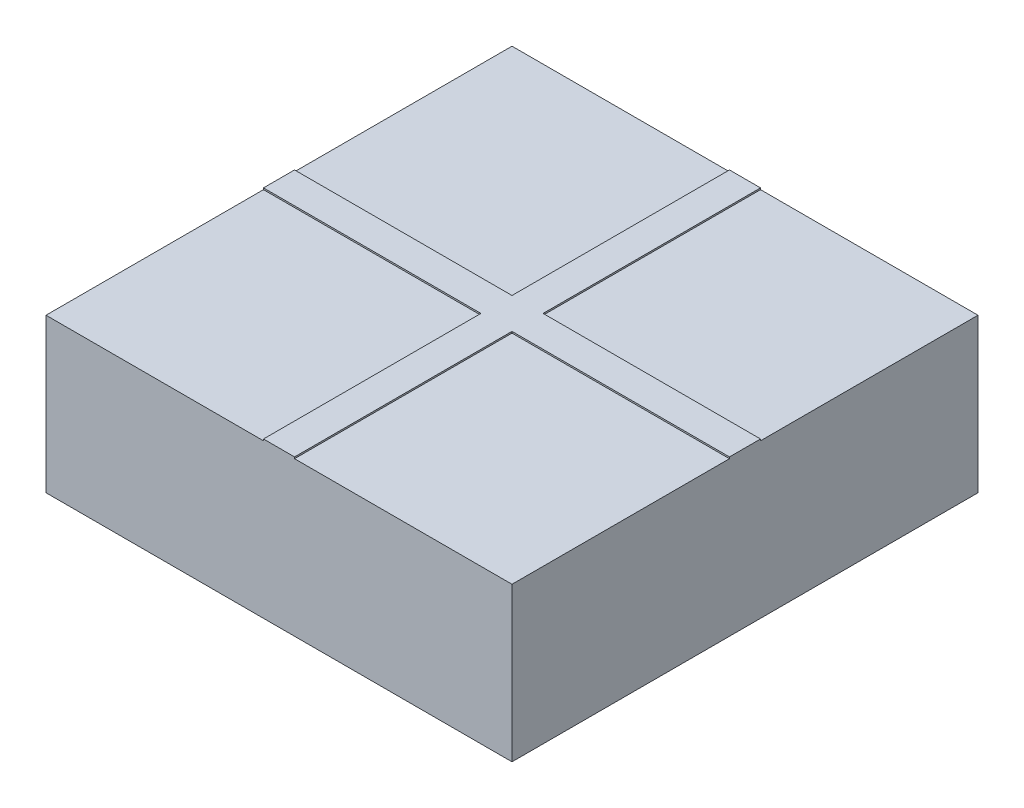
SolidWorks part; units mm, degrees
ref_plane "Спереди" through (0, 0, 0) normal (0, 0, 1) x (1, 0, 0)
ref_plane "Сверху" through (0, 0, 0) normal (0, 1, 0) x (1, 0, 0)
ref_plane "Справа" through (0, 0, 0) normal (1, 0, 0) x (0, 0, -1)
sketch "Эскиз1" plane through (0, 0, 0) normal (0, 1, 0) x (1, 0, 0)
  line L1 (-150, -150) -> (150, -150)
  line L2 (-150, -150) -> (-150, 150)
  line L3 (-150, 150) -> (150, 150)
  line L4 (150, -150) -> (150, 150)
  line L5 (-150, -150) -> (150, 150) construction
  line L6 (-150, 150) -> (150, -150) construction
  point P0 (0, 0)
  dimension "D1" = 300
extrude "Бобышка-Вытянуть1" add sketch "Эскиз1" along normal blind 90
sketch "Эскиз2" plane through (0, 90, 0) normal (0, 1, 0) x (1, 0, 0)
  line L1 (10, -150) -> (-10, -150)
  line L2 (10, -150) -> (10, 150)
  line L3 (10, 150) -> (-10, 150)
  line L4 (150, -150) -> (150, 150)
  line L5 (150, 150) -> (-150, 150)
  line L6 (-150, 150) -> (-150, -150)
  line L7 (-150, -150) -> (150, -150)
  line L8 (150, -150) -> (150, 150)
  line L9 (150, 150) -> (-150, 150)
  line L10 (-150, 150) -> (-150, -150)
  line L11 (-150, -150) -> (150, -150)
  line L12 (-10, -150) -> (-10, 150)
  line L13 (10, -150) -> (-10, 150) construction
  line L14 (10, 150) -> (-10, -150) construction
  line L15 (150, -10) -> (-150, -10)
  line L16 (150, -10) -> (150, 10)
  line L17 (150, 10) -> (-150, 10)
  line L18 (-150, -10) -> (-150, 10)
  line L19 (150, -10) -> (-150, 10) construction
  line L20 (150, 10) -> (-150, -10) construction
  point P2 (0, 0)
  point P10 (0, 0)
  point P15 (0, 0)
  dimension "D2" = 20
  dimension "D3" = 20
  dimension "D1" = 0
extrude "Бобышка-Вытянуть3" add sketch "Эскиз2" along normal blind 10 contours L12 L3 L2 L1 | L17 L18 L15 L16
sketch "Эскиз6" plane through (0, 90, 0) normal (0, 1, 0) x (1, 0, 0)
  line L0 (-150, -150) -> (-10, -150) construction
  line L1 (-10, -150) -> (-10, -10) construction
  line L2 (-10, -10) -> (-150, -10) construction
  line L3 (-150, -10) -> (-150, -150) construction
  line L4 (150, -150) -> (150, -10) construction
  line L5 (150, -10) -> (10, -10) construction
  line L6 (10, -10) -> (10, -150) construction
  line L7 (10, -150) -> (150, -150) construction
  line L8 (10, 150) -> (10, 10) construction
  line L9 (10, 10) -> (150, 10) construction
  line L10 (150, 10) -> (150, 150) construction
  line L11 (150, 150) -> (10, 150) construction
  line L12 (-150, 10) -> (-10, 10) construction
  line L13 (-10, 10) -> (-10, 150) construction
  line L14 (-10, 150) -> (-150, 150) construction
  line L15 (-150, 150) -> (-150, 10) construction
  line L16 (-150, -150) -> (-10, -150)
  line L17 (-10, -150) -> (-10, -10)
  line L18 (-10, -10) -> (-150, -10)
  line L19 (-150, -10) -> (-150, -150)
  line L20 (150, -150) -> (150, -10)
  line L21 (150, -10) -> (10, -10)
  line L22 (10, -10) -> (10, -150)
  line L23 (10, -150) -> (150, -150)
  line L24 (10, 150) -> (10, 10)
  line L25 (10, 10) -> (150, 10)
  line L26 (150, 10) -> (150, 150)
  line L27 (150, 150) -> (10, 150)
  line L28 (-150, 10) -> (-10, 10)
  line L29 (-10, 10) -> (-10, 150)
  line L30 (-10, 150) -> (-150, 150)
  line L31 (-150, 150) -> (-150, 10)
extrude "Бобышка-Вытянуть6" add sketch "Эскиз6" along normal blind 9
